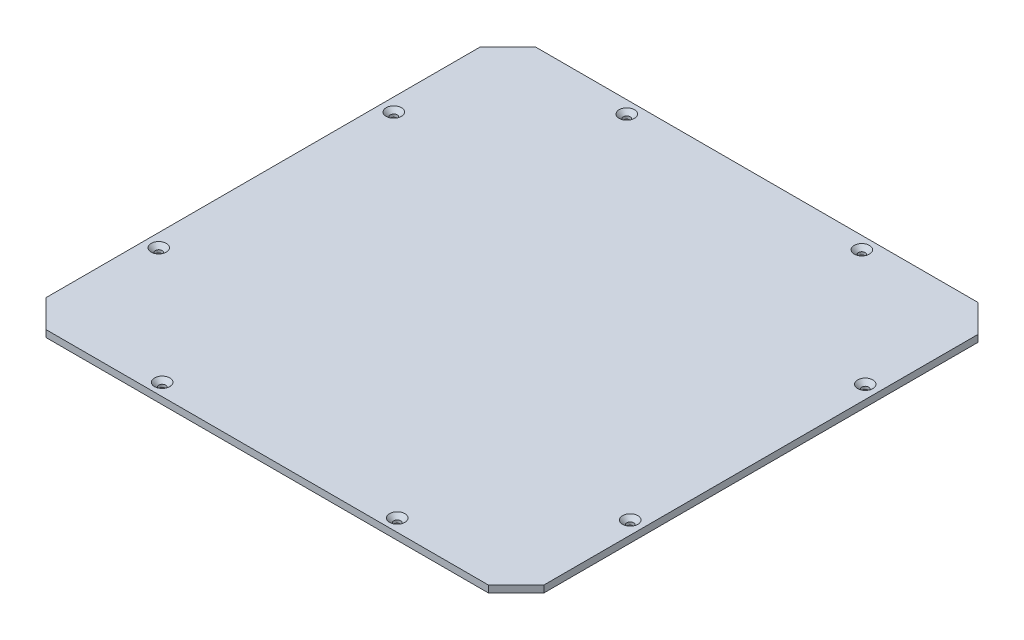
SolidWorks part; units mm, degrees
material "Клен"
ref_plane "Спереди" through (0, 0, 0) normal (0, 0, 1) x (1, 0, 0)
ref_plane "Сверху" through (0, 0, 0) normal (0, 1, 0) x (1, 0, 0)
ref_plane "Справа" through (0, 0, 0) normal (1, 0, 0) x (0, 0, -1)
sketch "Эскиз1" plane through (0, 0, 0) normal (0, 1, 0) x (1, 0, 0)
  line L1 (180, 177) -> (-180, 177)
  line L2 (180, 177) -> (180, -177)
  line L3 (180, -177) -> (-180, -177)
  line L4 (-180, 177) -> (-180, -177)
  line L5 (180, 177) -> (-180, -177) construction
  line L6 (180, -177) -> (-180, 177) construction
  point P0 (0, 0)
  dimension "D1" = 360
  dimension "D2" = 354
extrude "Бобышка-Вытянуть1" add sketch "Эскиз1" along normal blind 5
chamfer "Фаска1" distance 20 angle 45 4 edges at (180, 2.5, -177) (-180, 2.5, -177) (-180, 2.5, 177) (180, 2.5, 177)
sketch "Sketch1" plane through (0, 5, 0) normal (0, 1, 0) x (1, 0, 0)
  line L0 (0, 0) -> (0, 37.2083) construction
  line L1 (0, 0) -> (-45.8715, 0) construction
  circle A0 centre (85, -168) radius 2.5
  circle A1 centre (-85, -168) radius 2.5
  circle A2 centre (-170.5, -85) radius 2.5
  circle A3 centre (-170.5, 85) radius 2.5
  circle A4 centre (-85, 168) radius 2.5
  circle A5 centre (85, 168) radius 2.5
  circle A6 centre (170.5, 85) radius 2.5
  circle A7 centre (170.5, -85) radius 2.5
  dimension "D3" = 5
  dimension "D5" = 5
  dimension "D6" = 5
  dimension "D7" = 5
  dimension "D1" = 170.5
  dimension "D2" = 85
  dimension "D4" = 85
  dimension "D8" = 168
  dimension "D9" = 168
  dimension "D10" = 85
  dimension "D11" = 85
extrude "Cut-Extrude1" cut sketch "Sketch1" against normal blind 10
chamfer "Chamfer1" distance 3 angle 45 8 edges at (-85, 5, 165.5) (85, 5, 165.5) (170.5, 5, 82.5) (170.5, 5, -87.5) (85, 5, -165.5) (-85, 5, -165.5) (-170.5, 5, -82.5) (-170.5, 5, 87.5)
